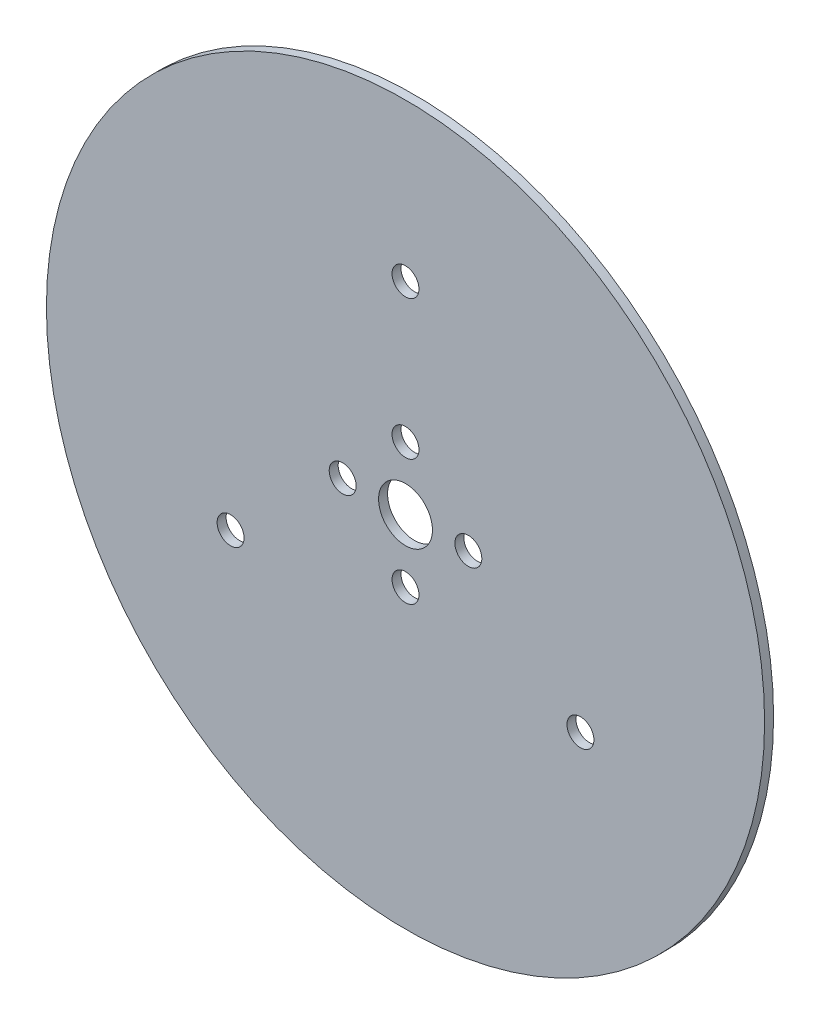
SolidWorks part; units mm, degrees
material "ABS"
ref_plane "前视基准面" through (0, 0, 0) normal (0, 0, 1) x (1, 0, 0)
ref_plane "上视基准面" through (0, 0, 0) normal (0, 1, 0) x (1, 0, 0)
ref_plane "右视基准面" through (0, 0, 0) normal (1, 0, 0) x (0, 0, -1)
sketch "草图1" plane through (0, 0, 0) normal (0, 0, 1) x (1, 0, 0)
  circle A0 centre (0, 0) radius 40
  circle A1 centre (0, 0) radius 2.5
  circle A2 centre (0, 0) radius 7 construction
  circle A3 centre (0, 7) radius 1.5
  circle A4 centre (7, 0) radius 1.5
  circle A5 centre (0, -7) radius 1.5
  circle A6 centre (-7, 0) radius 1.5
  dimension "D1" = 80
  dimension "D2" = 5
  dimension "D3" = 14
  dimension "D4" = 3
  dimension "D5" = 3
  dimension "D6" = 3
  dimension "D7" = 3
extrude "凸台-拉伸1" add sketch "草图1" along normal blind 1 contours A0 A6 A5 A4 A3 A1 | A2
sketch "草图2" plane through (0, 0, 1) normal (0, 0, 1) x (1, 0, 0)
  circle A0 centre (0, 0) radius 22.5 construction
  circle A1 centre (0, 22.5) radius 1.5
  circle A2 centre (19.4856, -11.25) radius 1.5
  circle A3 centre (-19.4856, -11.25) radius 1.5
  point P11 (0, 0)
  dimension "D1" = 45
  dimension "D2" = 3
  dimension "D3" = 3
extrude "切除-拉伸1" cut sketch "草图2" against normal blind 10
sketch "草图3" plane through (0, 0, 1) normal (0, 0, 1) x (1, 0, 0)
  circle A0 centre (0, 0) radius 3
extrude "切除-拉伸2" cut sketch "草图3" against normal blind 10
